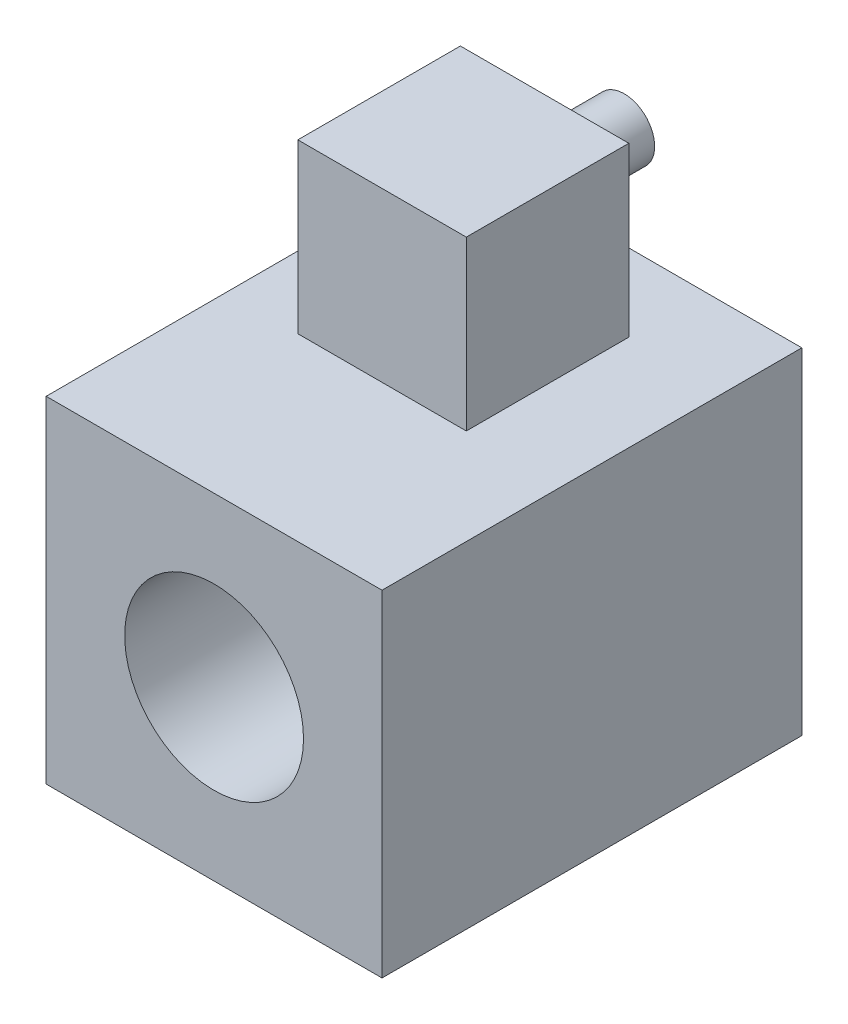
SolidWorks part; units mm, degrees
material "AISI 316  (SS)"
ref_plane "Front Plane" through (0, 0, 0) normal (0, 0, 1) x (1, 0, 0)
ref_plane "Top Plane" through (0, 0, 0) normal (0, 1, 0) x (1, 0, 0)
ref_plane "Right Plane" through (0, 0, 0) normal (1, 0, 0) x (0, 0, -1)
sketch "Sketch1" plane through (0, 0, 0) normal (0, 0, 1) x (1, 0, 0)
  line L1 (20, -20) -> (-20, -20)
  line L2 (20, -20) -> (20, 20)
  line L3 (20, 20) -> (-20, 20)
  line L4 (-20, -20) -> (-20, 20)
  line L5 (20, -20) -> (-20, 20) construction
  line L6 (20, 20) -> (-20, -20) construction
  point P0 (0, 0)
  dimension "D1" = 40
  dimension "D2" = 40
extrude "Boss-Extrude1" add sketch "Sketch1" along normal blind 50
sketch "Sketch2" plane through (0, 0, 50) normal (0, 0, 1) x (1, 0, 0)
  circle A0 centre (0, 0) radius 10.65
  dimension "D1" = 21.3
extrude "Cut-Extrude1" cut sketch "Sketch2" against normal through all
sketch "Sketch3" plane through (0, 20, 0) normal (0, 1, 0) x (1, 0, 0)
  line L1 (-11.4643, -28.5613) -> (8.5997, -28.5613)
  line L2 (-11.4643, -28.5613) -> (-11.4643, -9.2042)
  line L3 (-11.4643, -9.2042) -> (8.5997, -9.2042)
  line L4 (8.5997, -28.5613) -> (8.5997, -9.2042)
extrude "Boss-Extrude2" add sketch "Sketch3" along normal blind 20
sketch "Sketch4" plane through (0, 0, 9.2042) normal (0, 0, -1) x (-1, 0, 0)
  circle A0 centre (1.9449, 31.2141) radius 3.6194
extrude "Boss-Extrude3" add sketch "Sketch4" along normal blind 10
